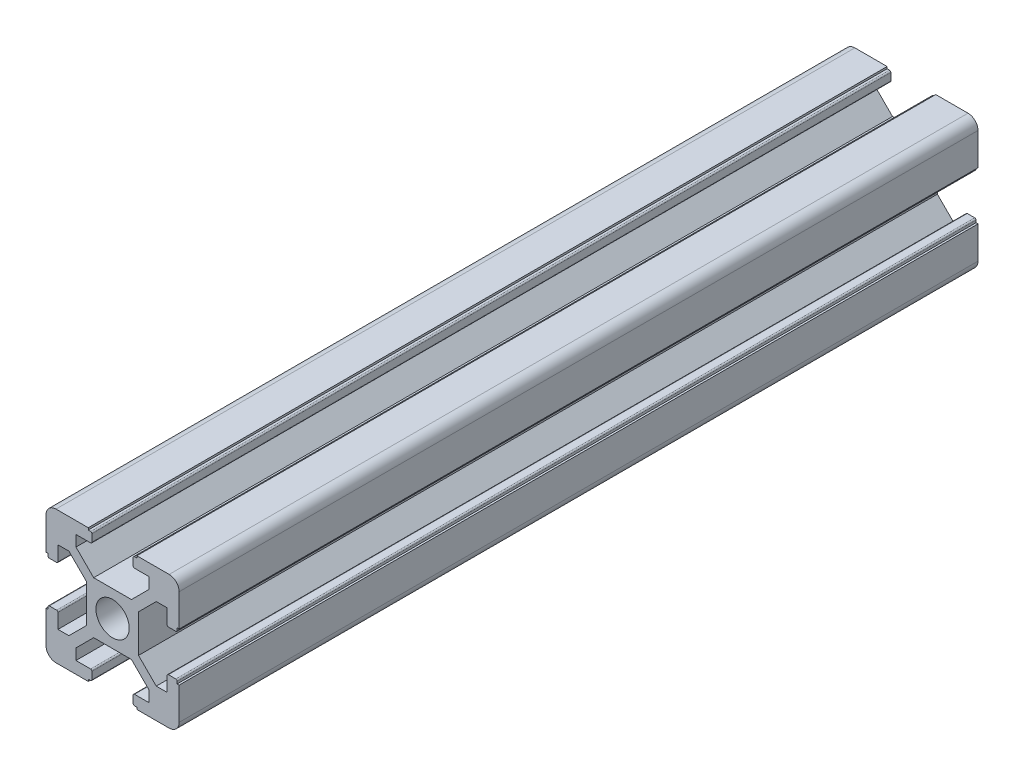
SolidWorks part; units mm, degrees
ref_plane "前视基准面" through (0, 0, 0) normal (0, 0, 1) x (1, 0, 0)
ref_plane "上视基准面" through (0, 0, 0) normal (0, 1, 0) x (1, 0, 0)
ref_plane "右视基准面" through (0, 0, 0) normal (1, 0, 0) x (0, 0, -1)
sketch "草图1" plane through (0, 0, 0) normal (0, 0, 1) x (1, 0, 0)
  line L0 (-17.5, 0) -> (33.5, 0) construction
  line L1 (0, 35.5833) -> (0, -31.0833) construction
  line L2 (3.65, 10) -> (8.5, 10)
  line L3 (10, 10) -> (10, -10) construction
  line L4 (-2.8393, 3.9) -> (2.8393, 3.9)
  line L5 (3.9, 2.8393) -> (3.9, -2.8393)
  line L6 (5.5, 8.2) -> (5.5, 6.5607)
  line L7 (3.9, 3.9) -> (10, 10) construction
  line L8 (4.4303, 3.3697) -> (6.5607, 5.5) construction
  line L9 (3.65, 10) -> (3.65, 8.2)
  line L10 (3.65, 8.2) -> (5.5, 8.2)
  line L11 (3.3697, 4.4303) -> (5.5, 6.5607) construction
  line L12 (5.5, 6.5607) -> (2.8393, 3.9)
  line L13 (6.5607, 5.5) -> (3.9, 2.8393)
  line L14 (3.3697, 4.4303) -> (9.4697, 10.5303) construction
  line L15 (4.4303, 3.3697) -> (10.5303, 9.4697) construction
  line L16 (8.2, 5.5) -> (6.5607, 5.5)
  line L17 (8.2, 3.65) -> (8.2, 5.5)
  line L18 (10, 3.65) -> (10, 8.5)
  line L19 (10, 3.65) -> (8.2, 3.65)
  line L20 (-3.3697, 4.4303) -> (-5.5, 6.5607) construction
  line L21 (-4.4303, 3.3697) -> (-6.5607, 5.5) construction
  line L22 (-3.9, 3.9) -> (-10, 10) construction
  line L23 (-10, 10) -> (-10, -10) construction
  line L24 (-10, 3.65) -> (-8.2, 3.65)
  line L25 (-10, 3.65) -> (-10, 8.5)
  line L26 (-8.2, 3.65) -> (-8.2, 5.5)
  line L27 (-8.2, 5.5) -> (-6.5607, 5.5)
  line L28 (-6.5607, 5.5) -> (-3.9, 2.8393)
  line L29 (-5.5, 6.5607) -> (-2.8393, 3.9)
  line L30 (-3.65, 8.2) -> (-5.5, 8.2)
  line L31 (-3.65, 10) -> (-3.65, 8.2)
  line L32 (-5.5, 8.2) -> (-5.5, 6.5607)
  line L33 (-3.9, 2.8393) -> (-3.9, -2.8393)
  line L34 (-3.65, 10) -> (-8.5, 10)
  line L35 (-3.9, -3.9) -> (-10, -10) construction
  line L36 (-4.4303, -3.3697) -> (-6.5607, -5.5) construction
  line L37 (-3.3697, -4.4303) -> (-5.5, -6.5607) construction
  line L38 (3.3697, -4.4303) -> (5.5, -6.5607) construction
  line L39 (4.4303, -3.3697) -> (6.5607, -5.5) construction
  line L40 (3.9, -3.9) -> (10, -10) construction
  line L41 (-3.65, -10) -> (-8.5, -10)
  line L42 (-5.5, -8.2) -> (-5.5, -6.5607)
  line L43 (-3.65, -10) -> (-3.65, -8.2)
  line L44 (-3.65, -8.2) -> (-5.5, -8.2)
  line L45 (-5.5, -6.5607) -> (-2.8393, -3.9)
  line L46 (-6.5607, -5.5) -> (-3.9, -2.8393)
  line L47 (-8.2, -5.5) -> (-6.5607, -5.5)
  line L48 (-8.2, -3.65) -> (-8.2, -5.5)
  line L49 (-10, -3.65) -> (-10, -8.5)
  line L50 (-10, -3.65) -> (-8.2, -3.65)
  line L51 (10, -3.65) -> (8.2, -3.65)
  line L52 (10, -3.65) -> (10, -8.5)
  line L53 (8.2, -3.65) -> (8.2, -5.5)
  line L54 (8.2, -5.5) -> (6.5607, -5.5)
  line L55 (6.5607, -5.5) -> (3.9, -2.8393)
  line L56 (5.5, -6.5607) -> (2.8393, -3.9)
  line L57 (3.65, -8.2) -> (5.5, -8.2)
  line L58 (3.65, -10) -> (3.65, -8.2)
  line L59 (5.5, -8.2) -> (5.5, -6.5607)
  line L60 (-2.8393, -3.9) -> (2.8393, -3.9)
  line L61 (3.65, -10) -> (8.5, -10)
  circle A0 centre (0, 0) radius 2.5
  arc A1 (-8.5, -10) -> (-10, -8.5) centre (-8.5, -8.5) cw
  arc A2 (10, -8.5) -> (8.5, -10) centre (8.5, -8.5) cw
  arc A3 (8.5, 10) -> (10, 8.5) centre (8.5, 8.5) cw
  arc A4 (-10, 8.5) -> (-8.5, 10) centre (-8.5, 8.5) cw
  point P13 (0, -3.9)
  point P42 (0, 3.9)
  point P43 (-10, 0)
  point P54 (10, 0)
  point P56 (-3.9, 0)
  point P70 (3.9, 0)
  dimension "D3" = 5
  dimension "D10" = 1.5
  dimension "D1" = 7.3
  dimension "D2" = 10
  dimension "D4" = 3.9
  dimension "D5" = 3.9
  dimension "D8" = 1.8
  dimension "D9" = 0.75
  dimension "D6" = 11
  dimension "D7" = 10
  dimension "D11" = 45
  dimension "D12" = 2.8393
extrude "凸台-拉伸2" add sketch "草图1" along normal blind 120 contours L34 A4 L25 L24 L26 L27 L28 L33 L46 L47 L48 L50 L49 A1 L41 L43 L44 L42 L45 L60 L56 L59 L57 L58 L61 A2 L52 L51 L53 L54 L55 L5 L13 L16 L17 L19 L18 A3 L2 L9 L10 L6 L12 L4 L29 L32 L30 L31
sketch "草图3" plane through (0, 0, 120) normal (0, 0, 1) x (1, 0, 0)
  line L0 (-12.6954, 0) -> (11.5012, 0) construction
  line L1 (0, 10.0863) -> (0, -11.0469) construction
  line L2 (-3.65, 8.2) -> (-3.3, 8.2)
  line L3 (3.65, 8.2) -> (3.6528, 8.2568)
  line L4 (-3.1, 8.4) -> (-3.1, 9.5)
  line L5 (3.65, 9.7) -> (3.65, 8.2)
  line L6 (-3.3, 9.7) -> (-3.65, 9.7)
  line L7 (-3.65, 8.2) -> (-3.65, 10) construction
  line L8 (-3.65, 9.7) -> (-3.65, 8.2)
  line L9 (-3.65, 8.2) -> (-3.6528, 8.2568)
  line L10 (3.3, 9.7) -> (3.65, 9.7)
  line L11 (3.1, 8.4) -> (3.1, 9.5)
  line L12 (3.65, 8.2) -> (3.3, 8.2)
  line L13 (3.65, -8.2) -> (3.3, -8.2)
  line L14 (3.1, -8.4) -> (3.1, -9.5)
  line L15 (3.3, -9.7) -> (3.65, -9.7)
  line L16 (-3.65, -8.2) -> (-3.6528, -8.2568)
  line L17 (-3.65, -9.7) -> (-3.65, -8.2)
  line L18 (-3.3, -9.7) -> (-3.65, -9.7)
  line L19 (3.65, -9.7) -> (3.65, -8.2)
  line L20 (-3.1, -8.4) -> (-3.1, -9.5)
  line L21 (3.65, -8.2) -> (3.6528, -8.2568)
  line L22 (-3.65, -8.2) -> (-3.3, -8.2)
  line L23 (0, 0) -> (9.5607, 9.5607) construction
  line L24 (-8.2, -3.65) -> (-8.2, -3.3)
  line L25 (-8.4, -3.1) -> (-9.5, -3.1)
  line L26 (-9.7, -3.3) -> (-9.7, -3.65)
  line L27 (-9.7, -3.65) -> (-8.2, -3.65)
  line L28 (-8.2, -3.65) -> (-8.2568, -3.6528)
  line L29 (8.2, 3.65) -> (8.2, 3.3)
  line L30 (8.4, 3.1) -> (9.5, 3.1)
  line L31 (9.7, 3.3) -> (9.7, 3.65)
  line L32 (9.7, 3.65) -> (8.2, 3.65)
  line L33 (8.2, 3.65) -> (8.2568, 3.6528)
  line L34 (-8.2, 3.65) -> (-8.2568, 3.6528)
  line L35 (-9.7, 3.65) -> (-8.2, 3.65)
  line L36 (-9.7, 3.3) -> (-9.7, 3.65)
  line L37 (-8.4, 3.1) -> (-9.5, 3.1)
  line L38 (-8.2, 3.65) -> (-8.2, 3.3)
  line L39 (8.2, -3.65) -> (8.2568, -3.6528)
  line L40 (9.7, -3.65) -> (8.2, -3.65)
  line L41 (9.7, -3.3) -> (9.7, -3.65)
  line L42 (8.4, -3.1) -> (9.5, -3.1)
  line L43 (8.2, -3.65) -> (8.2, -3.3)
  arc A0 (-3.1, 9.5) -> (-3.3, 9.7) centre (-3.3, 9.5) ccw
  arc A1 (-3.3, 8.2) -> (-3.1, 8.4) centre (-3.3, 8.4) ccw
  arc A2 (3.3, 8.2) -> (3.1, 8.4) centre (3.3, 8.4) cw
  arc A3 (3.1, 9.5) -> (3.3, 9.7) centre (3.3, 9.5) cw
  arc A4 (3.1, -9.5) -> (3.3, -9.7) centre (3.3, -9.5) ccw
  arc A5 (3.3, -8.2) -> (3.1, -8.4) centre (3.3, -8.4) ccw
  arc A6 (-3.3, -8.2) -> (-3.1, -8.4) centre (-3.3, -8.4) cw
  arc A7 (-3.1, -9.5) -> (-3.3, -9.7) centre (-3.3, -9.5) cw
  arc A8 (10, 8.5) -> (8.5, 10) centre (8.5, 8.5) ccw construction
  arc A9 (-9.5, -3.1) -> (-9.7, -3.3) centre (-9.5, -3.3) ccw
  arc A10 (-8.2, -3.3) -> (-8.4, -3.1) centre (-8.4, -3.3) ccw
  arc A11 (9.5, 3.1) -> (9.7, 3.3) centre (9.5, 3.3) ccw
  arc A12 (8.2, 3.3) -> (8.4, 3.1) centre (8.4, 3.3) ccw
  arc A13 (-8.2, 3.3) -> (-8.4, 3.1) centre (-8.4, 3.3) cw
  arc A14 (-9.5, 3.1) -> (-9.7, 3.3) centre (-9.5, 3.3) cw
  arc A15 (8.2, -3.3) -> (8.4, -3.1) centre (8.4, -3.3) cw
  arc A16 (9.5, -3.1) -> (9.7, -3.3) centre (9.5, -3.3) cw
  point P16 (-3.1, 9.7)
  point P19 (-3.1, 8.2)
  point P29 (3.1, 8.2)
  point P30 (3.1, 9.7)
  point P49 (3.1, -9.7)
  point P50 (3.1, -8.2)
  point P51 (-3.1, -8.2)
  point P52 (-3.1, -9.7)
  point P67 (-9.7, -3.1)
  point P68 (-8.2, -3.1)
  point P78 (9.7, 3.1)
  point P79 (8.2, 3.1)
  point P89 (-8.2, 3.1)
  point P90 (-9.7, 3.1)
  point P100 (8.2, -3.1)
  point P101 (9.7, -3.1)
  line M1 (-3.65, -10) -> (-3.65, -8.2)
  line M9 (3.65, -8.2) -> (3.65, -10)
  line M21 (8.2, 3.65) -> (10, 3.65)
  line M25 (3.65, 10) -> (3.65, 8.2)
  line M33 (-3.65, 8.2) -> (-3.65, 10)
  line M37 (-10, 3.65) -> (-8.2, 3.65)
  dimension "D3" = 0.2
  dimension "D1" = 6.2
  dimension "D2" = 1.5
extrude "凸台-拉伸3" add sketch "草图3" against normal blind 120 contours A14 L37 A13 L38 L36 M37 | L2 A1 L4 A0 L6 M33 | A3 L11 A2 L12 L10 M25 | L29 A12 L30 A11 L31 M21 | L13 A5 L14 A4 L15 M9 | A7 L20 A6 L22 L18 M1 | L43 A15 L42 A16 L41 L40 | L24 A10 L25 A9 L26 L27
